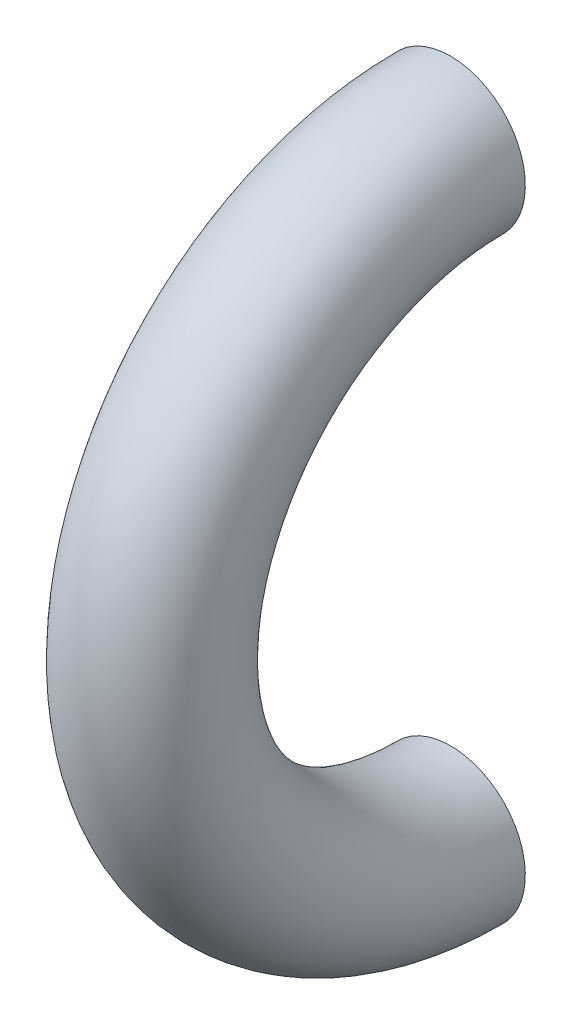
SolidWorks part; units mm, degrees
ref_plane "前视基准面" through (0, 0, 0) normal (0, 0, 1) x (1, 0, 0)
ref_plane "上视基准面" through (0, 0, 0) normal (0, 1, 0) x (1, 0, 0)
ref_plane "右视基准面" through (0, 0, 0) normal (1, 0, 0) x (0, 0, -1)
other "Configuration Table"
sketch "草图1" plane through (0, 0, 0) normal (0, 0, 1) x (1, 0, 0)
  circle A0 centre (0, 0) radius 20
sketch "草图2" plane through (0, 0, 0) normal (1, 0, 0) x (0, 0, -1)
  arc A0 (0, 0) -> (0, -160) centre (0, -80) ccw
sweep "扫描2" add profiles "草图1" path "草图2"
